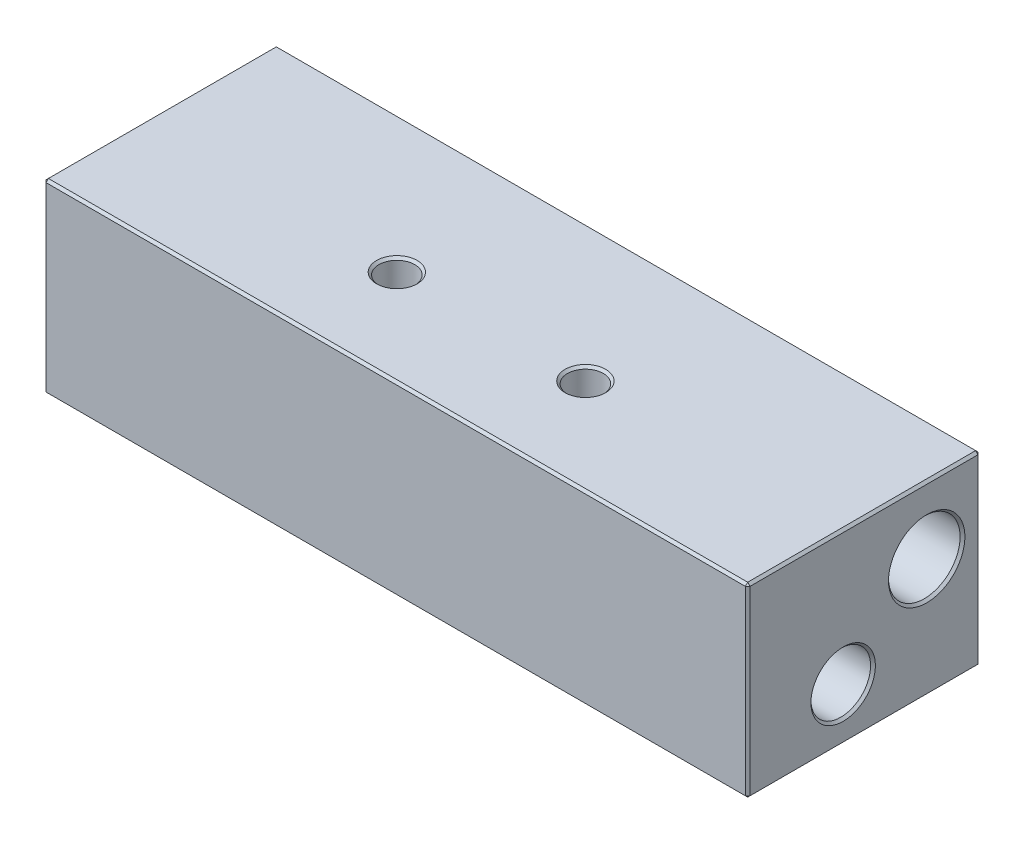
SolidWorks part; units mm, degrees
material "6061 Alloy"
ref_plane "Front Plane" through (0, 0, 0) normal (0, 0, 1) x (1, 0, 0)
ref_plane "Top Plane" through (0, 0, 0) normal (0, 1, 0) x (1, 0, 0)
ref_plane "Right Plane" through (0, 0, 0) normal (1, 0, 0) x (0, 0, -1)
sketch "Sketch1" plane through (0, 0, 0) normal (0, 0, 1) x (1, 0, 0)
  line L1 (0, 0) -> (59, 0)
  line L2 (0, 0) -> (0, 15.6)
  line L3 (0, 15.6) -> (59, 15.6)
  line L4 (59, 0) -> (59, 15.6)
  dimension "D1" = 15.6
  dimension "D2" = 59
extrude "Boss-Extrude1" add sketch "Sketch1" along normal blind 19.5
sketch "Sketch2" plane through (0, 0, 0) normal (-1, 0, 0) x (0, 0, 1)
  line L0 (19.5, 0) -> (0, 0) construction
  line L1 (0, 15.6) -> (0, 0) construction
  circle A0 centre (10.4, 10.7) radius 3
  circle A1 centre (4.5, 4.6) radius 3
  dimension "D5" = 6
  dimension "D6" = 6
  dimension "D1" = 4.6
  dimension "D2" = 4.5
  dimension "D3" = 10.4
  dimension "D4" = 10.7
extrude "Cut-Extrude1" cut sketch "Sketch2" against normal blind 2
sketch "Sketch3" plane through (59, 0, 0) normal (1, 0, 0) x (0, 0, -1)
  line L1 (-19.5, 0) -> (0, 0) construction
  line L2 (0, 0) -> (0, 15.6) construction
  circle A0 centre (-4.5, 10) radius 3
  circle A1 centre (-11.5, 4.4) radius 2.5
  dimension "D3" = 6
  dimension "D6" = 5
  dimension "D1" = 10
  dimension "D2" = 4.5
  dimension "D4" = 4.4
  dimension "D5" = 11.5
extrude "Cut-Extrude2" cut sketch "Sketch3" against normal blind 5
sketch "Sketch4" plane through (0, 0, 0) normal (0, -1, 0) x (1, 0, 0)
  line L0 (0, 0) -> (59, 0) construction
  line L1 (29.5, 0) -> (29.5, 19.5) construction
  line L2 (0, 19.5) -> (59, 19.5) construction
  circle A0 centre (21.6, 11.5) radius 1.5
  circle A1 centre (37.4, 11.5) radius 1.5
  dimension "D1" = 3
  dimension "D2" = 3
  dimension "D3" = 15.8
  dimension "D4" = 11.5
  dimension "D5" = 7.9
extrude "Cut-Extrude3" cut sketch "Sketch4" against normal through all
chamfer "Chamfer1" distance 0.2 angle 45 19 edges at (29.5, 0, 0) (59, 7.8, 0) (29.5, 15.6, 0) (0, 7.8, 0) (29.5, 15.6, 19.5) (59, 15.6, 9.75) (59, 7.8, 19.5) (59, 0, 9.75) (29.5, 0, 19.5) (0, 15.6, 9.75) (0, 7.8, 19.5) (0, 0, 9.75) (59, 4.4, 9) (37.4, 15.6, 10) (21.6, 15.6, 10) (37.4, 0, 10) (21.6, 0, 10) (59, 10, 1.5) (54, 10, 1.5)
